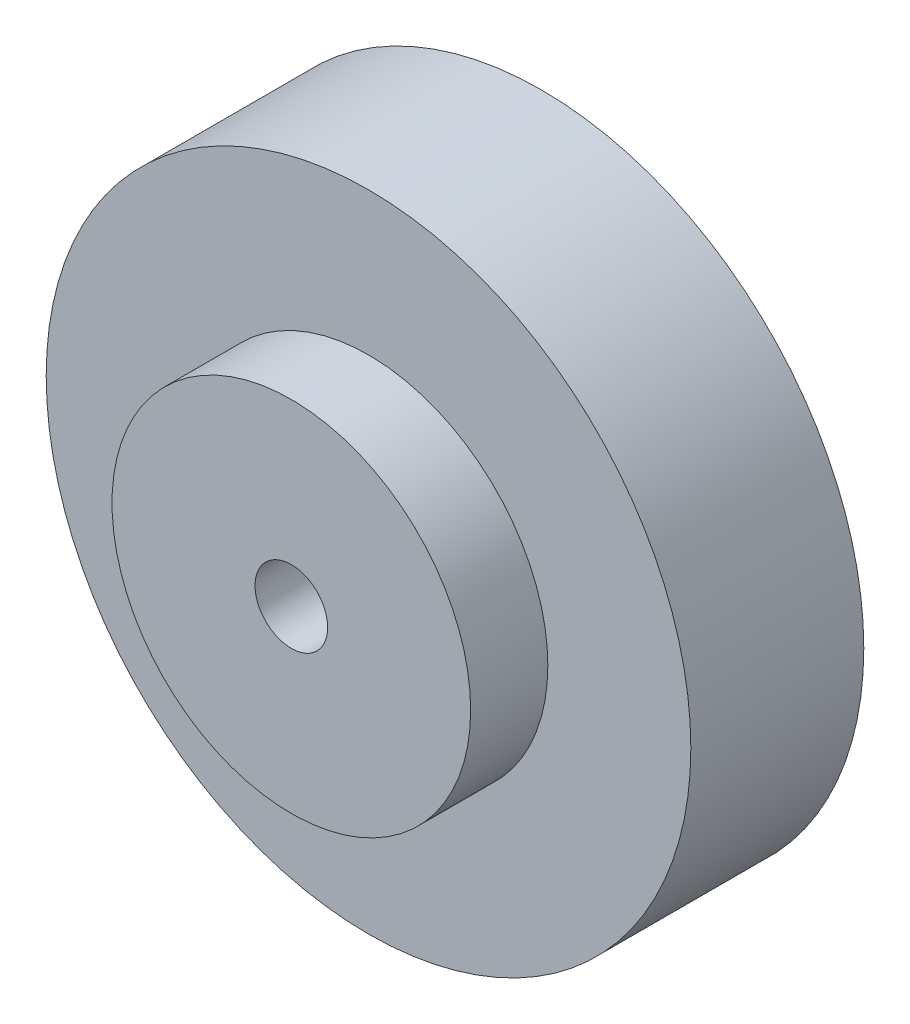
SolidWorks part; units mm, degrees
ref_plane "Front Plane" through (0, 0, 0) normal (0, 0, 1) x (1, 0, 0)
ref_plane "Top Plane" through (0, 0, 0) normal (0, 1, 0) x (1, 0, 0)
ref_plane "Right Plane" through (0, 0, 0) normal (1, 0, 0) x (0, 0, -1)
sketch "Sketch1" plane through (0, 0, 0) normal (0, 0, 1) x (1, 0, 0)
  circle A0 centre (0, 0) radius 14.2
  dimension "D1" = 28.4
extrude "Boss-Extrude1" add sketch "Sketch1" along normal blind 7.62
sketch "Sketch2" plane through (0, 0, 7.62) normal (0, 0, 1) x (1, 0, 0)
  circle A0 centre (0, 0) radius 7.9
  dimension "D1" = 15.8
extrude "Boss-Extrude2" add sketch "Sketch2" along normal blind 3.4
sketch "Sketch3" plane through (0, 0, 0) normal (0, 0, -1) x (-1, 0, 0)
  circle A0 centre (0, 0) radius 1.6
  dimension "D1" = 3.2
extrude "Cut-Extrude1" cut sketch "Sketch3" against normal through all
